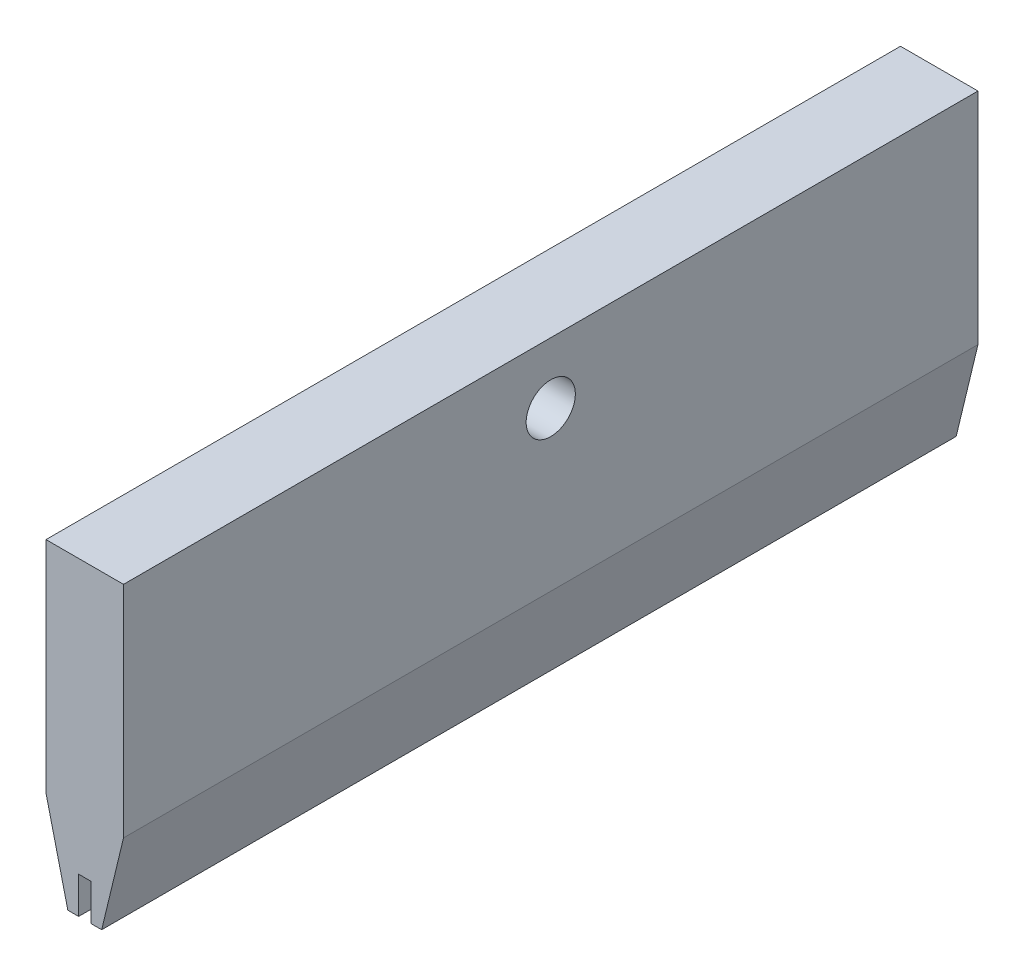
SolidWorks part; units mm, degrees
ref_plane "Alzado" through (0, 0, 0) normal (0, 0, 1) x (1, 0, 0)
ref_plane "Planta" through (0, 0, 0) normal (0, 1, 0) x (1, 0, 0)
ref_plane "Vista lateral" through (0, 0, 0) normal (1, 0, 0) x (0, 0, -1)
sketch "Croquis1" plane through (0, 0, 0) normal (0, 0, 1) x (1, 0, 0)
  line L0 (-2.7732, -25.4) -> (-6.35, -10.5764)
  line L1 (2.7732, -25.4) -> (1, -25.4)
  line L2 (6.35, -10.5764) -> (6.35, 25.4)
  line L3 (6.35, 25.4) -> (-6.35, 25.4)
  line L4 (-6.35, -10.5764) -> (-6.35, 25.4)
  line L5 (6.35, -25.4) -> (-6.35, 25.4) construction
  line L6 (6.35, 25.4) -> (-6.35, -25.4) construction
  line L7 (-1, -19.4) -> (1, -19.4)
  line L8 (1, -19.4) -> (1, -25.4)
  line L9 (1, -25.4) -> (2.7732, -25.4)
  line L10 (2.7732, -25.4) -> (6.35, -10.5764)
  line L12 (0, 0) -> (0, -37.7252) construction
  line L13 (-1, -19.4) -> (-1, -25.4)
  line L14 (-1, -25.4) -> (-2.7732, -25.4)
  point P0 (0, 0)
  point P17 (0, -19.4)
  dimension "D1" = 50.8
  dimension "D2" = 12.7
  dimension "D3" = 1
  dimension "D4" = 6
extrude "Saliente-Extruir1" add sketch "Croquis1" along normal blind 140 contours L14 L13 L7 L8 L1 L10 L2 L3 L4 L0
sketch "Croquis2" plane through (6.35, 0, 0) normal (1, 0, 0) x (0, 0, -1)
  line L0 (-140, 25.4) -> (0, 25.4) construction
  circle A0 centre (-70, 15.4) radius 4.0296
  dimension "D1" = 10
extrude "Cortar-Extruir1" cut sketch "Croquis2" against normal blind 140
